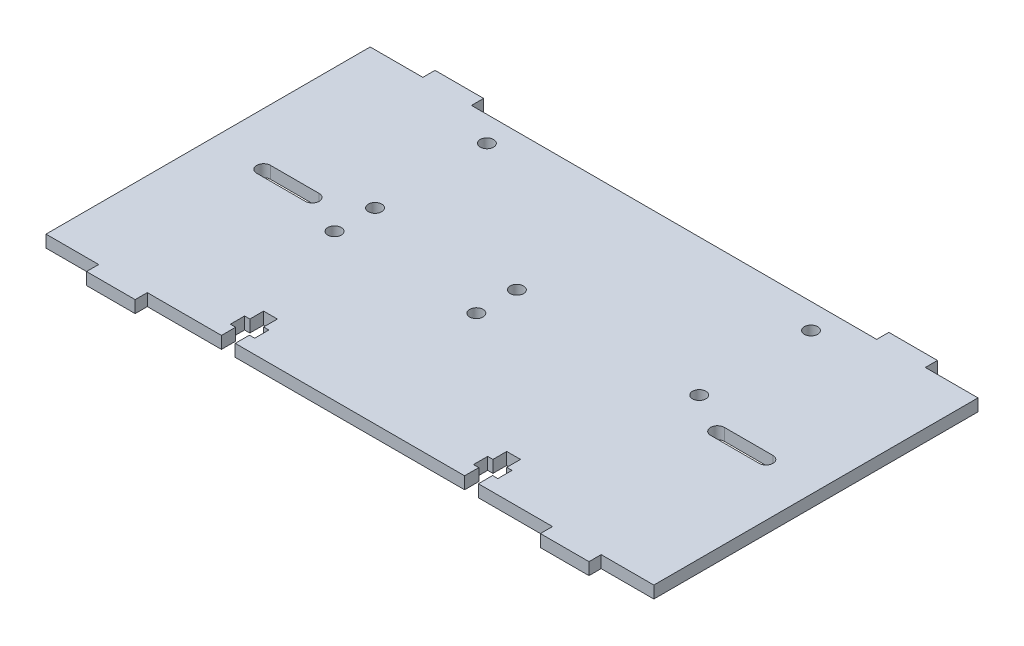
SolidWorks part; units mm, degrees
material "Thornel Mat VMA"
ref_plane "前视基准面" through (0, 0, 0) normal (0, 0, 1) x (1, 0, 0)
ref_plane "上视基准面" through (0, 0, 0) normal (0, 1, 0) x (1, 0, 0)
ref_plane "右视基准面" through (0, 0, 0) normal (1, 0, 0) x (0, 0, -1)
sketch "草图1" plane through (0, 0, 0) normal (0, 1, 0) x (1, 0, 0)
  line L0 (0, 40) -> (150, 40) construction
  line L1 (0, 0) -> (13, 0)
  line L2 (0, 0) -> (0, 80)
  line L3 (0, 80) -> (13, 80)
  line L4 (150, 0) -> (150, 80)
  line L5 (75, 70) -> (75, 0) construction
  line L6 (125, 0) -> (125, -3)
  line L8 (13, 0) -> (13, -3)
  line L9 (13, -3) -> (25, -3)
  line L10 (25, 0) -> (25, -3)
  line L11 (137, -3) -> (125, -3)
  line L12 (137, 0) -> (137, -3)
  line L13 (137, 80) -> (137, 83)
  line L14 (137, 83) -> (125, 83)
  line L15 (25, 80) -> (25, 83)
  line L16 (13, 83) -> (25, 83)
  line L17 (13, 80) -> (13, 83)
  line L18 (125, 80) -> (125, 83)
  line L19 (25, 80) -> (125, 80)
  line L20 (137, 80) -> (150, 80)
  line L21 (137, 0) -> (150, 0)
  line L22 (25, 0) -> (125, 0)
  line L23 (13, 40.7) -> (25, 40.7) construction
  line L24 (13, 42.4) -> (25, 42.4)
  line L25 (13, 39) -> (25, 39)
  line L26 (125, 40.7) -> (137, 40.7) construction
  line L27 (125, 42.4) -> (137, 42.4)
  line L28 (125, 39) -> (137, 39)
  line L29 (35, 80) -> (35, 40) construction
  line L30 (35, 60) -> (115, 60) construction
  line L31 (115, 80) -> (115, 40) construction
  arc A0 (13, 42.4) -> (13, 39) centre (13, 40.7) ccw
  arc A1 (25, 39) -> (25, 42.4) centre (25, 40.7) ccw
  arc A2 (125, 42.4) -> (125, 39) centre (125, 40.7) ccw
  arc A3 (137, 39) -> (137, 42.4) centre (137, 40.7) ccw
  circle A4 centre (35, 73.8) radius 1.65
  circle A5 centre (35, 46.2) radius 1.65
  circle A6 centre (115, 46.2) radius 1.65
  circle A7 centre (115, 73.8) radius 1.65
  circle A14 centre (35, 36.2) radius 1.65
  circle A15 centre (70, 46.2) radius 1.65
  circle A16 centre (70, 36.2) radius 1.65
  point P27 (19, 40.7)
  point P32 (131, 40.7)
  point P53 (0, 0)
  point P54 (0, 0)
  dimension "D13" = 3.3
  dimension "D14" = 27.6
  dimension "D15" = 35
  dimension "D16" = 10
  dimension "D17" = 35
  dimension "D18" = 10
  dimension "D19" = 3.3
  dimension "D20" = 3.3
  dimension "D21" = 3.3
  dimension "D1" = 150
  dimension "D2" = 80
  dimension "D3" = 12
  dimension "D4" = 3
  dimension "D5" = 100
  dimension "D6" = 37.6
  dimension "D7" = 3.4
  dimension "D8" = 3.4
  dimension "D9" = 12
  dimension "D10" = 100
  dimension "D11" = 40
  dimension "D12" = 40
extrude "凸台-拉伸1" add sketch "草图1" along normal blind 3
sketch "草图2" plane through (0, 3, 0) normal (0, 1, 0) x (1, 0, 0)
  line L0 (75, 80) -> (75, 0) construction
  line L1 (125, 80) -> (25, 80) construction
  line L2 (25, 0) -> (125, 0) construction
  line L3 (43.3, 0) -> (43.3, 3.5)
  line L4 (43.3, 3.5) -> (42, 3.5)
  line L5 (42, 3.5) -> (42, 7)
  line L6 (42, 7) -> (43.3, 7)
  line L7 (43.3, 7) -> (43.3, 10.4)
  line L8 (43.3, 10.4) -> (46.7, 10.4)
  line L9 (46.7, 10.4) -> (46.7, 7)
  line L10 (46.7, 7) -> (48, 7)
  line L11 (48, 7) -> (48, 3.5)
  line L12 (48, 3.5) -> (46.7, 3.5)
  line L13 (46.7, 3.5) -> (46.7, 0)
  line L14 (46.7, 0) -> (43.3, 0)
  line L15 (45, 0) -> (45, 10.4) construction
  line L16 (105, 0) -> (105, 10.4) construction
  line L17 (103.3, 0) -> (106.7, 0)
  line L18 (103.3, 3.5) -> (103.3, 0)
  line L19 (102, 3.5) -> (103.3, 3.5)
  line L20 (102, 7) -> (102, 3.5)
  line L21 (103.3, 7) -> (102, 7)
  line L22 (103.3, 10.4) -> (103.3, 7)
  line L23 (106.7, 10.4) -> (103.3, 10.4)
  line L24 (106.7, 7) -> (106.7, 10.4)
  line L25 (108, 7) -> (106.7, 7)
  line L26 (108, 3.5) -> (108, 7)
  line L27 (106.7, 3.5) -> (108, 3.5)
  line L28 (106.7, 0) -> (106.7, 3.5)
  dimension "D1" = 3.4
  dimension "D2" = 3.4
  dimension "D3" = 3.5
  dimension "D4" = 3.5
  dimension "D5" = 6
  dimension "D6" = 30
extrude "切除-拉伸1" cut sketch "草图2" against normal through all
